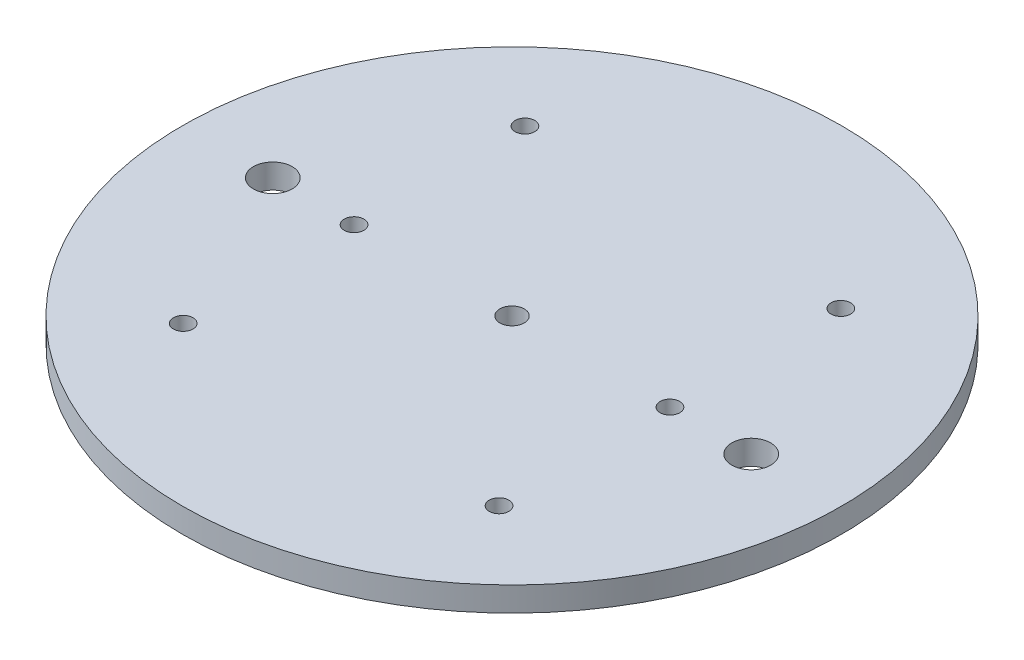
SolidWorks part; units mm, degrees
material "Malleable Cast Iron"
ref_plane "Front Plane" through (0, 0, 0) normal (0, 0, 1) x (1, 0, 0)
ref_plane "Top Plane" through (0, 0, 0) normal (0, 1, 0) x (1, 0, 0)
ref_plane "Right Plane" through (0, 0, 0) normal (1, 0, 0) x (0, 0, -1)
sketch "Sketch12" plane through (0, 0, 0) normal (0, 1, 0) x (1, 0, 0)
  line B0 (-31.369, -69.0517) -> (-31.369, 69.0517) construction
  line B1 (50.8, -69.0517) -> (50.8, 69.0517) construction
  line B2 (50.8, -69.0517) -> (-50.8, -69.0517) construction
  line B3 (-50.8, -69.0517) -> (-50.8, 69.0517) construction
  line B4 (50.8, 69.0517) -> (-50.8, 69.0517) construction
  line B5 (31.369, 69.0517) -> (31.369, -69.0517) construction
  circle B6 centre (0, 0) radius 85.725
  line B7 (-31.369, 0) -> (31.369, 0) construction
  line B8 (41.0845, -69.0517) -> (41.0845, 69.0517) construction
  line B9 (31.369, 0) -> (50.8, 0) construction
  line B10 (-31.369, 0) -> (-50.8, 0) construction
  line B11 (-41.0845, 44.45) -> (41.0845, -44.45) construction
  line B12 (-41.0845, -69.0517) -> (-41.0845, 69.0517) construction
  line B13 (-41.0845, -44.45) -> (41.0845, 44.45) construction
  line B14 (-50.8, 0) -> (-85.725, 0) construction
  line B15 (50.8, 0) -> (85.725, 0) construction
  line B16 (0, -85.725) -> (0, 85.725) construction
sketch_block_instance "swivel plate-3"
sketch_block "swivel plate" parameters "D1"=171.45, "D2"=32.9884, "D3"=88.1371, "D4"=89.3617, "D5"=152.4754
sketch "Sketch1" plane through (0, 0, 0) normal (0, 1, 0) x (1, 0, 0)
  circle A0 centre (0, 0) radius 85.725 construction
  circle A1 centre (0, 0) radius 85.725
extrude "Boss-Extrude1" add sketch "Sketch1" along normal blind 6.35
hole_wizard "3/8 Clearance Hole1" positions "Sketch6" profile "Sketch7" hole size "3/8" standard "ANSI Inch" end condition through all
sketch "Sketch6" plane through (0, 6.35, 0) normal (0, 1, 0) x (0.9997, 0, 0.0242)
  point P20 (-62.2117, -1.5089)
  point P22 (62.2117, 1.5089)
sketch "Sketch7" plane through (-62.23, 6.35, 0) normal (1, 0, 0) x (0, 0, 1)
  line L0 (0, 0) -> (0, 6.35)
  line L1 (0, 6.35) -> (5.0419, 6.35)
  line L2 (5.0419, 6.35) -> (5.0419, 0)
  line L5 (5.0419, 0) -> (0, 0)
  line L11 (0, -6.35) -> (0, 107.95) construction
  dimension "Thru Hole Dia." = 10.0838
  dimension "Thru Hole Depth" = 6.35
hole_wizard "1/4 (0.25) Clearance Dowel Hole1" positions "Sketch8" profile "Sketch9" hole size "1/4" standard "ANSI Inch" end condition through all
sketch "Sketch8" plane through (43.3774, 6.35, -259.2845) normal (0, 1, 0) x (0.9888, 0, -0.1489)
  point P3 (-81.5106, -249.9322)
sketch "Sketch9" plane through (0, 6.35, 0) normal (1, 0, 0) x (0, 0, 1)
  line L0 (0, 0) -> (0, 6.35)
  line L1 (0, 6.35) -> (3.175, 6.35)
  line L2 (3.175, 6.35) -> (3.175, 0)
  line L3 (3.175, 0) -> (0, 0)
  line L4 (0, -6.35) -> (0, 107.95) construction
  dimension "Thru Hole Dia." = 6.35
  dimension "Thru Hole Depth" = 6.35
hole_wizard "#10 Clearance Hole1" positions "Sketch10" profile "Sketch11" hole size "#10" standard "ANSI Inch" end condition up to next
sketch "Sketch10" plane through (43.3774, 0, -259.2845) normal (0, -1, 0) x (-0.9888, 0, 0.1489)
  point P22 (143.0465, -240.6638)
  point P24 (19.9747, -259.2005)
  point P26 (40.8843, -256.0512)
  point P28 (34.2641, -212.0969)
  point P30 (115.5166, -199.859)
  point P32 (128.7571, -287.7674)
  point P34 (115.5166, -199.859)
  point P35 (122.1369, -243.8132)
  point P37 (128.7571, -287.7674)
  point P38 (47.5046, -300.0054)
sketch "Sketch11" plane through (-62.23, 0, 0) normal (1, 0, 0) x (0, 0, -1)
  line L0 (0, 0) -> (0, 6.35)
  line L1 (0, 6.35) -> (2.5527, 6.35)
  line L2 (2.5527, 6.35) -> (2.5527, 0)
  line L5 (2.5527, 0) -> (0, 0)
  line L11 (0, -6.35) -> (0, 107.95) construction
  dimension "Thru Hole Dia." = 5.1054
  dimension "Thru Hole Depth" = 6.35
equation "\"delta-z\" = 1.5"
equation "\"total-height\" = 3.28"
equation "\"mid-height\" = 1.5"
equation "\"jaw-width\" = 4"
equation "\"jaw-height\" = \"total-height\" - \"mid-height\""
equation "\"max-tube-diam\" = 3.5"
equation "\"v-block-notch-height\" = 1.5"
equation "\"v-block-notch-angle\" = 120"
equation "\"jaw-travel\" = 4.45"
equation "\"rib-top-width\" = 0.5"
equation "\"rib-side-width\" = 0.5"
equation "\"quarter-twenty-close-clearance\" = .257"
equation "\"box-way-width\" = 1.5"
equation "\"box-way-depth\" = 1.5"
equation "\"screw-OD\" = .625"
equation "\"screw-reduced-diam\" = .47"
equation "\"pressure-plate-OD\" = 6.75"
equation "\"D1@swivel plate\"=\"pressure-plate-OD\""
equation "\"D2@swivel plate\"=\"jaw-width\""
equation "\"D3@swivel plate\"=2.47"
